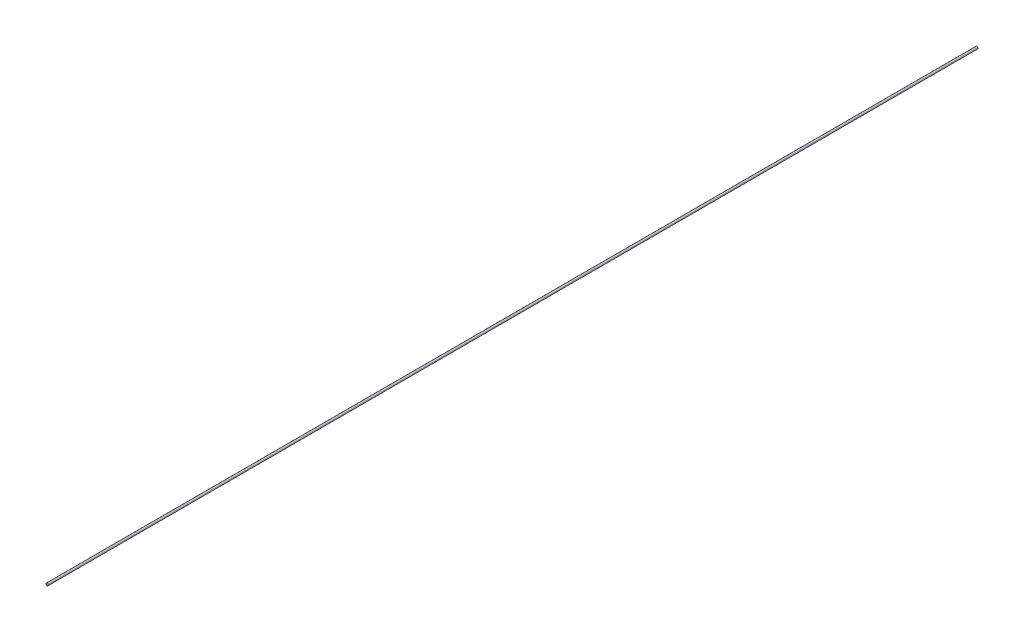
SolidWorks part; units mm, degrees
material "Nylon 101"
ref_plane "Front Plane" through (0, 0, 0) normal (0, 0, 1) x (1, 0, 0)
ref_plane "Top Plane" through (0, 0, 0) normal (0, 1, 0) x (1, 0, 0)
ref_plane "Right Plane" through (0, 0, 0) normal (1, 0, 0) x (0, 0, -1)
sketch "Sketch2" plane through (0, 0, 0) normal (0, 0, 1) x (1, 0, 0)
  circle A0 centre (0, 0) radius 0.2159
  dimension "D1" = 0.4318
extrude "Boss-Extrude1" add sketch "Sketch2" along normal blind 177.8
